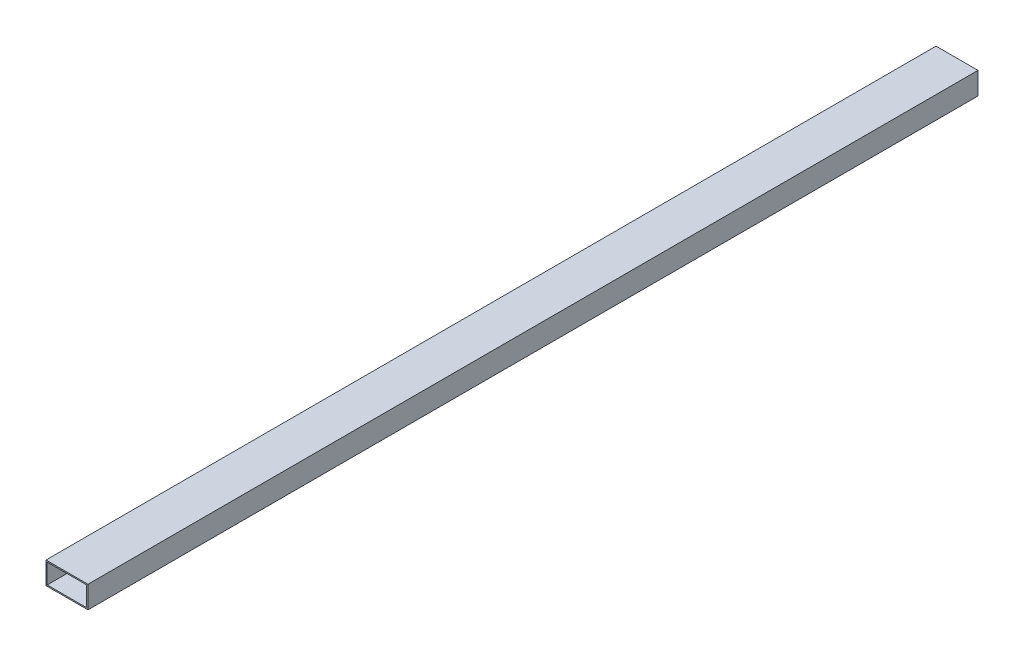
SolidWorks part; units mm, degrees
ref_plane "Front Plane" through (0, 0, 0) normal (0, 0, 1) x (1, 0, 0)
ref_plane "Top Plane" through (0, 0, 0) normal (0, 1, 0) x (1, 0, 0)
ref_plane "Right Plane" through (0, 0, 0) normal (1, 0, 0) x (0, 0, -1)
sketch "Sketch1" plane through (0, 0, 0) normal (0, 0, 1) x (1, 0, 0)
  line L1 (0, 0) -> (50.8, 0)
  line L2 (0, 0) -> (0, -25.4)
  line L3 (0, -25.4) -> (50.8, -25.4)
  line L4 (50.8, 0) -> (50.8, -25.4)
  dimension "D1" = 50.8
  dimension "D2" = 25.4
extrude "Extrude-Thin1" add sketch "Sketch1" along normal blind 1144.5875 thin thin type one direction wall 1.5875
